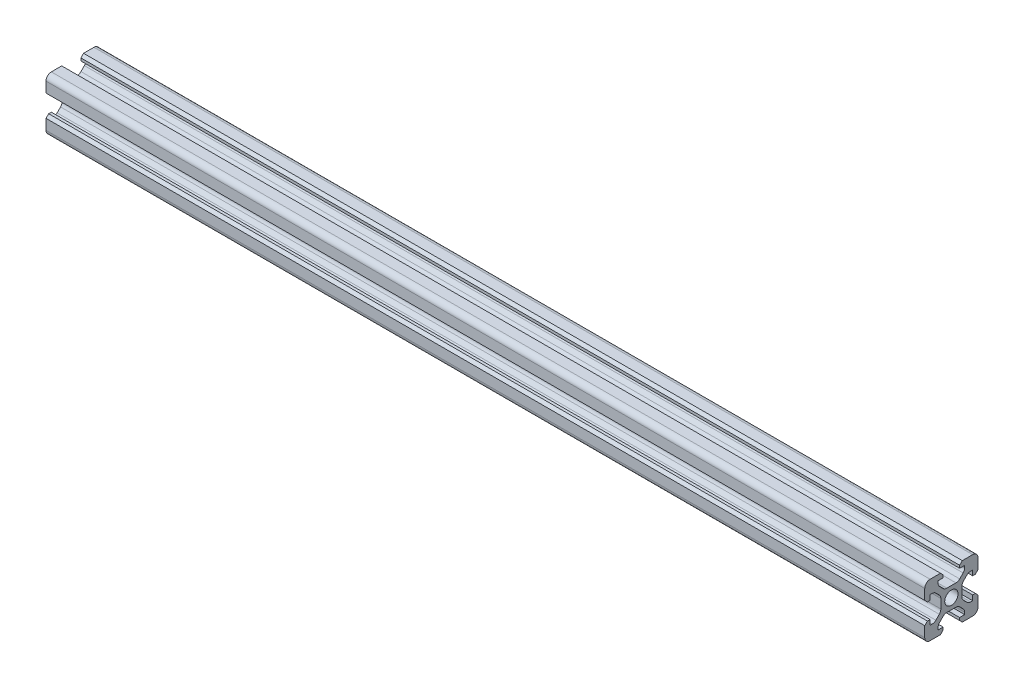
SolidWorks part; units mm, degrees
ref_plane "Front Plane" through (0, 0, 0) normal (0, 0, 1) x (1, 0, 0)
ref_plane "Top Plane" through (0, 0, 0) normal (0, 1, 0) x (1, 0, 0)
ref_plane "Right Plane" through (0, 0, 0) normal (1, 0, 0) x (0, 0, -1)
sketch "Sketch1" plane through (0, 0, 0) normal (1, 0, 0) x (0, 0, -1)
  line B0 (-4.1, 10) -> (-8, 10)
  line B1 (-3.1, 8) -> (-3.1, 9)
  line B2 (9, -3.1) -> (10, -4.1)
  line B3 (3.1, 8) -> (3.1, 9)
  line B4 (4.4142, 5.8284) -> (3.1236, 4.5379)
  line B5 (10, 4.1) -> (9, 3.1)
  line B6 (5, 8) -> (3.1, 8)
  line B7 (5, 7.2426) -> (5, 8)
  line B8 (-3.1, 8) -> (-5, 8)
  line B9 (-5, 7.2426) -> (-5, 8)
  line B10 (4.1, 10) -> (3.1, 9)
  line B11 (5.8284, -4.4142) -> (4.5379, -3.1236)
  line B12 (7.2426, -5) -> (8, -5)
  line B13 (8, -3.1) -> (8, -5)
  line B14 (7.2426, 5) -> (8, 5)
  line B15 (8, 10) -> (4.1, 10)
  line B16 (-1.7094, 3.9521) -> (1.7094, 3.9521)
  line B17 (8, 5) -> (8, 3.1)
  line B18 (8, 3.1) -> (9, 3.1)
  line B19 (-3.1, 9) -> (-4.1, 10)
  line B20 (8, -3.1) -> (9, -3.1)
  line B21 (3.9521, 1.7094) -> (3.9521, -1.7094)
  line B22 (-3.1236, 4.5379) -> (-4.4142, 5.8284)
  line B23 (10, -4.1) -> (10, -8)
  line B24 (4.5379, 3.1236) -> (5.8284, 4.4142)
  line B25 (-3.1, -9) -> (-4.1, -10)
  line B26 (8, -10) -> (4.1, -10)
  line B27 (4.1, -10) -> (3.1, -9)
  line B28 (-4.4142, -5.8284) -> (-3.1236, -4.5379)
  line B29 (-5, -7.2426) -> (-5, -8)
  line B30 (-3.1, -8) -> (-5, -8)
  line B31 (5, -7.2426) -> (5, -8)
  line B32 (5, -8) -> (3.1, -8)
  line B33 (3.1, -8) -> (3.1, -9)
  line B34 (-3.1, -8) -> (-3.1, -9)
  line B35 (1.7094, -3.9521) -> (-1.7094, -3.9521)
  line B36 (-4.1, -10) -> (-8, -10)
  line B37 (3.1236, -4.5379) -> (4.4142, -5.8284)
  line B38 (-9, 3.1) -> (-10, 4.1)
  line B39 (-10, -8) -> (-10, -4.1)
  line B40 (-10, -4.1) -> (-9, -3.1)
  line B41 (-5.8284, 4.4142) -> (-4.5379, 3.1236)
  line B42 (-7.2426, 5) -> (-8, 5)
  line B43 (-8, 3.1) -> (-8, 5)
  line B44 (-7.2426, -5) -> (-8, -5)
  line B45 (-8, -5) -> (-8, -3.1)
  line B46 (-8, -3.1) -> (-9, -3.1)
  line B47 (-8, 3.1) -> (-9, 3.1)
  line B48 (-3.9521, -1.7094) -> (-3.9521, 1.7094)
  line B49 (-10, 8) -> (-10, 4.1)
  line B50 (-4.5379, -3.1236) -> (-5.8284, -4.4142)
  line B51 (10, 8) -> (10, 4.1)
  circle B52 centre (0, 0) radius 2.5
  arc B53 (-4.5379, 3.1236) -> (-3.9521, 1.7094) centre (-5.9521, 1.7094) cw
  arc B54 (-5.8284, 4.4142) -> (-7.2426, 5) centre (-7.2426, 3) ccw
  arc B55 (-5, 7.2426) -> (-4.4142, 5.8284) centre (-3, 7.2426) ccw
  arc B56 (5, 7.2426) -> (4.4142, 5.8284) centre (3, 7.2426) cw
  arc B57 (7.2426, 5) -> (5.8284, 4.4142) centre (7.2426, 3) ccw
  arc B58 (5.8284, -4.4142) -> (7.2426, -5) centre (7.2426, -3) ccw
  arc B59 (5, -7.2426) -> (4.4142, -5.8284) centre (3, -7.2426) ccw
  arc B60 (-4.4142, -5.8284) -> (-5, -7.2426) centre (-3, -7.2426) ccw
  arc B61 (-7.2426, -5) -> (-5.8284, -4.4142) centre (-7.2426, -3) ccw
  arc B62 (-3.9521, -1.7094) -> (-4.5379, -3.1236) centre (-5.9521, -1.7094) cw
  arc B63 (-3.1236, -4.5379) -> (-1.7094, -3.9521) centre (-1.7094, -5.9521) cw
  arc B64 (1.7094, -3.9521) -> (3.1236, -4.5379) centre (1.7094, -5.9521) cw
  arc B65 (4.5379, -3.1236) -> (3.9521, -1.7094) centre (5.9521, -1.7094) cw
  arc B66 (3.9521, 1.7094) -> (4.5379, 3.1236) centre (5.9521, 1.7094) cw
  arc B67 (1.7094, 3.9521) -> (3.1236, 4.5379) centre (1.7094, 5.9521) ccw
  arc B68 (-1.7094, 3.9521) -> (-3.1236, 4.5379) centre (-1.7094, 5.9521) cw
  arc B69 (10, 8) -> (8, 10) centre (8, 8) ccw
  arc B70 (-8, -10) -> (-10, -8) centre (-8, -8) cw
  arc B71 (10, -8) -> (8, -10) centre (8, -8) cw
  arc B72 (-8, 10) -> (-10, 8) centre (-8, 8) ccw
sketch_block_instance "2020-1"
sketch_block "2020" parameters "D1"=2
extrude "Boss-Extrude1" add sketch "Sketch1" along normal blind 330
